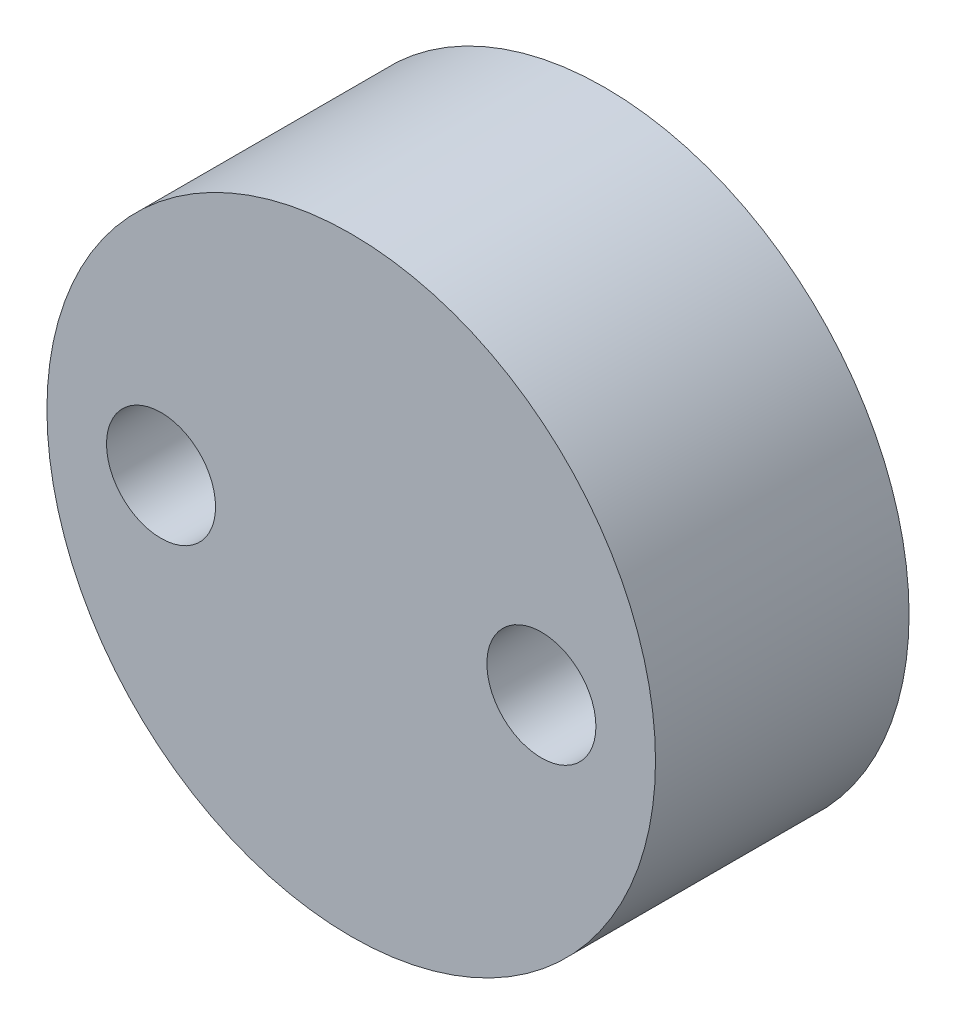
SolidWorks part; units mm, degrees
material "5052-H34"
ref_plane "正面" through (0, 0, 0) normal (0, 0, 1) x (1, 0, 0)
ref_plane "平面" through (0, 0, 0) normal (0, 1, 0) x (1, 0, 0)
ref_plane "右側面" through (0, 0, 0) normal (1, 0, 0) x (0, 0, -1)
sketch "ｽｹｯﾁ1" plane through (0, 0, 0) normal (0, 0, 1) x (1, 0, 0)
  circle A0 centre (0, 0) radius 12
  dimension "D1" = 24
extrude "ﾎﾞｽ - 押し出し1" add sketch "ｽｹｯﾁ1" along normal blind 10
sketch "ｽｹｯﾁ2" plane through (0, 0, 10) normal (0, 0, 1) x (1, 0, 0)
  line L0 (0, 12) -> (0, 0) construction
  line L1 (0, 0) -> (12, 0) construction
  circle A0 centre (0, 0) radius 12 construction
  circle A2 centre (7.5, 0) radius 2.15
  circle A3 centre (-7.5, 0) radius 2.15
  dimension "D1" = 4.3
  dimension "D2" = 15
extrude "ｶｯﾄ - 押し出し1" cut sketch "ｽｹｯﾁ2" against normal up to surface (10 mm away) up to face at (12, 0, 0)
